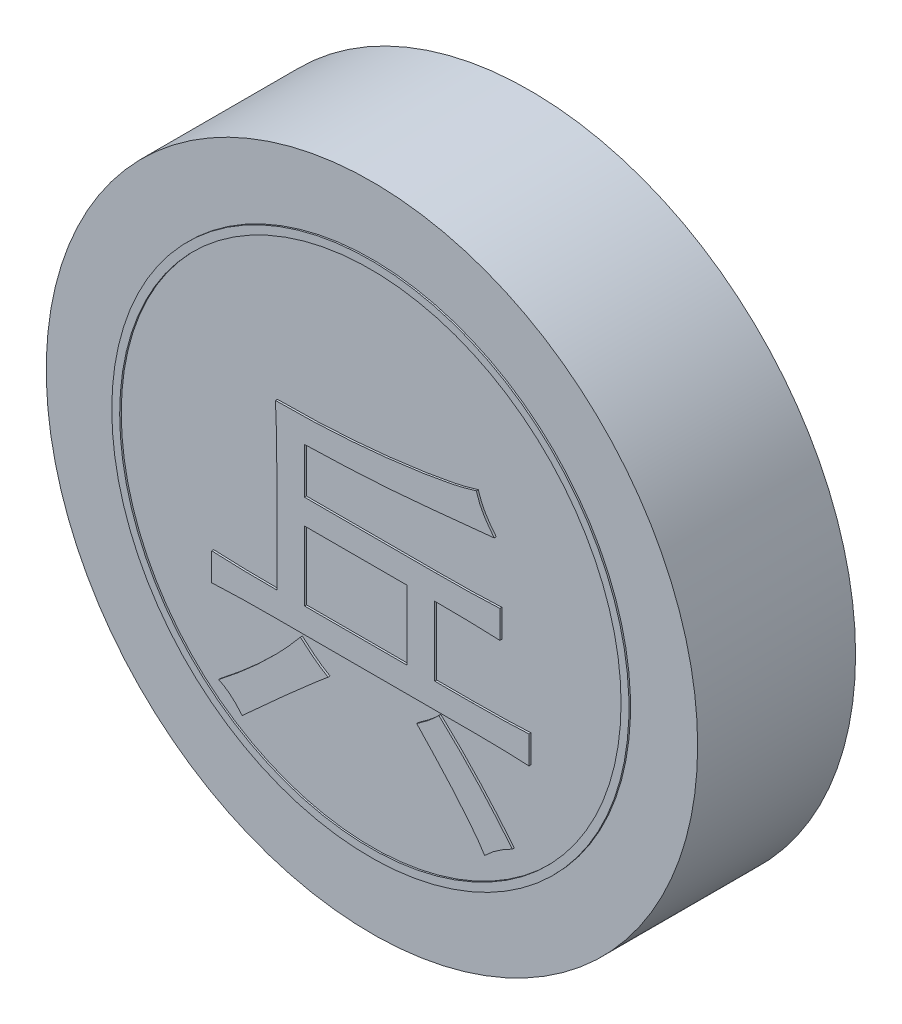
SolidWorks part; units mm, degrees
ref_plane "前视基准面" through (0, 0, 0) normal (0, 0, 1) x (1, 0, 0)
ref_plane "上视基准面" through (0, 0, 0) normal (0, 1, 0) x (1, 0, 0)
ref_plane "右视基准面" through (0, 0, 0) normal (1, 0, 0) x (0, 0, -1)
other "Configuration Table"
sketch "草图1" plane through (0, 0, 0) normal (0, 0, 1) x (1, 0, 0)
  circle A0 centre (0, 0) radius 16.5
  dimension "D1" = 33
extrude "Diameter33_Height8" add sketch "草图1" against normal blind 8
sketch "草图2" plane through (0, 0, 0) normal (0, 0, 1) x (1, 0, 0)
  text T0 "兵" font "SimHei" height 12
extrude "Character_兵" add sketch "草图2" along normal blind 0.1
sketch "草图3" plane through (0, 0, 0) normal (0, 0, 1) x (1, 0, 0)
  circle A0 centre (0, 0) radius 13.1
  circle A1 centre (0, 0) radius 12.7
extrude "Ink_ring" add sketch "草图3" along normal blind 0.08
